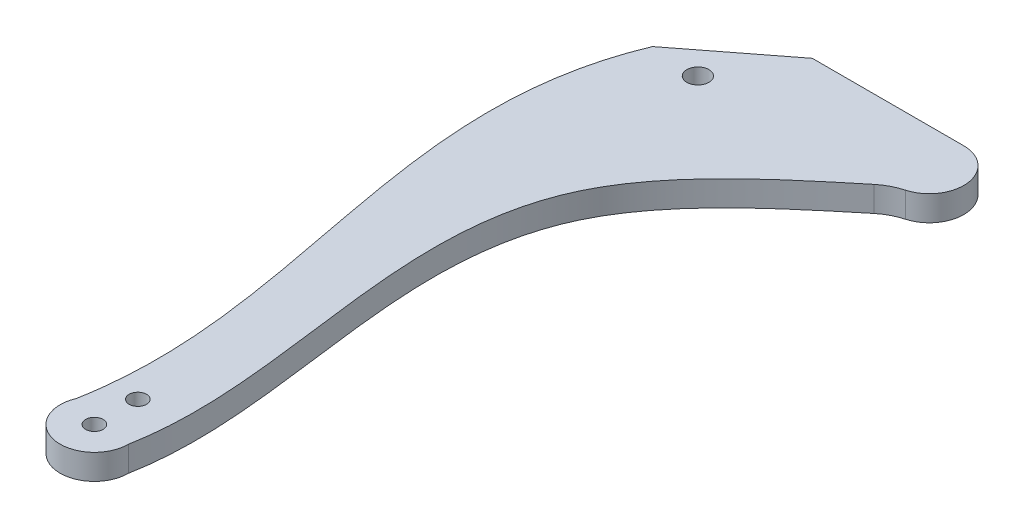
SolidWorks part; units mm, degrees
ref_plane "Front Plane" through (0, 0, 0) normal (0, 0, 1) x (1, 0, 0)
ref_plane "Top Plane" through (0, 0, 0) normal (0, 1, 0) x (1, 0, 0)
ref_plane "Right Plane" through (0, 0, 0) normal (1, 0, 0) x (0, 0, -1)
sketch "Sketch1" plane through (0, 0, 0) normal (0, 1, 0) x (1, 0, 0)
  line L0 (-16.1449, 8.454) -> (10.8777, 8.454)
  line L1 (-16.1449, 8.454) -> (-32.2175, -3.9875)
  line L2 (-23.6206, -4.479) -> (-23.6206, -112.139) construction
  circle A0 centre (-23.6206, -4.479) radius 1.975
  arc A1 (12.5128, -3.6032) -> (10.8777, 8.454) centre (10.8777, 2.3145) ccw
  circle A2 centre (-23.6206, -112.139) radius 1.555
  circle A3 centre (-23.6206, -104.379) radius 1.555
  arc A4 (-29.2395, -109.7574) -> (-17.5177, -112.139) centre (-23.6206, -112.139) ccw
  arc A5 (12.5128, -3.6032) -> (8.8241, -5.5185) centre (15.1759, -13.2421) ccw
  spline S0 degree 3 poles (-32.2175, -3.9875) (-42.2065, -27.8278) (-29.5614, -63.9823) (-27.3902, -99.665) (-29.2395, -109.7574) knots 0 0 0 0 0.696305 0.977824 0.977824 0.977824 0.977824
  spline S1 degree 3 poles (8.8241, -5.5185) (4.9325, -8.7188) (-4.696, -16.5859) (-31.4891, -46.9438) (-12.8947, -87.3265) (-17.5177, -112.139) knots 0.023478 0.023478 0.023478 0.023478 0.154944 0.330833 1 1 1 1
  dimension "D1" = 10
  dimension "D4" = 3.11
  dimension "D5" = 3.11
  dimension "D2" = 107.66
  dimension "D3" = 99.9
extrude "Boss-Extrude1" add sketch "Sketch1" along normal blind 4.5
